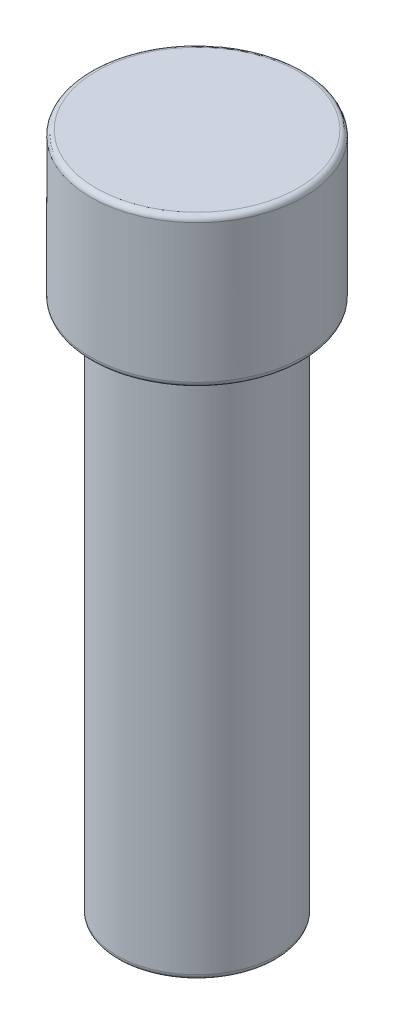
SolidWorks part; units mm, degrees
ref_plane "Plan de face" through (0, 0, 0) normal (0, 0, 1) x (1, 0, 0)
ref_plane "Plan de dessus" through (0, 0, 0) normal (0, 1, 0) x (1, 0, 0)
ref_plane "Plan de droite" through (0, 0, 0) normal (1, 0, 0) x (0, 0, -1)
sketch "Esquisse1" plane through (0, 0, 0) normal (0, 0, 1) x (1, 0, 0)
  line L0 (0, 0) -> (0, 25.6) construction
  line L1 (0, 25.6) -> (4, 25.6)
  line L2 (4, 25.6) -> (4, 20)
  line L3 (4, 20) -> (3, 20)
  line L4 (3, 20) -> (3, 0)
  line L5 (3, 0) -> (0, 0)
  line L6 (0, 0) -> (0, 25.6)
  dimension "D1" = 6
  dimension "D2" = 8
  dimension "D3" = 20
  dimension "D4" = 5.6
revolve "Révolution1" add sketch "Esquisse1" angle 360 about L0
hole_wizard "Trou taraudé M2.51" positions "Esquisse3" profile "Esquisse2" tap size "M2.5" standard "DIN"
sketch "Esquisse3" plane through (0, 0, 0) normal (0, -1, 0) x (-1, 0, 0)
  point P0 (0, 0)
sketch "Esquisse2" plane through (0, 0, 0) normal (1, 0, 0) x (0, 0, -1)
  line L0 (0, 0) -> (0, 9.8659)
  line L1 (0, 9.8659) -> (1.025, 9.25)
  line L2 (1.025, 9.25) -> (1.025, 0)
  line L5 (1.025, 0) -> (0, 0)
  line L10 (0, 9.8659) -> (-1.025, 9.25) construction
  line L11 (0, -6.35) -> (0, 107.95) construction
  dimension "Diamètre du trou pour taraudage" = 2.05
  dimension "Profondeur du trou pour taraudage" = 9.25
  dimension "Angle de pointe" = 118
cosmetic thread "Filetage de perçage1" parameters "D1"=7, "D2"=2.5
fillet "Congé1" radius 0.2 3 edges at (0, 0, -3) (0, 25.6, -4) (0, 20, -4)
